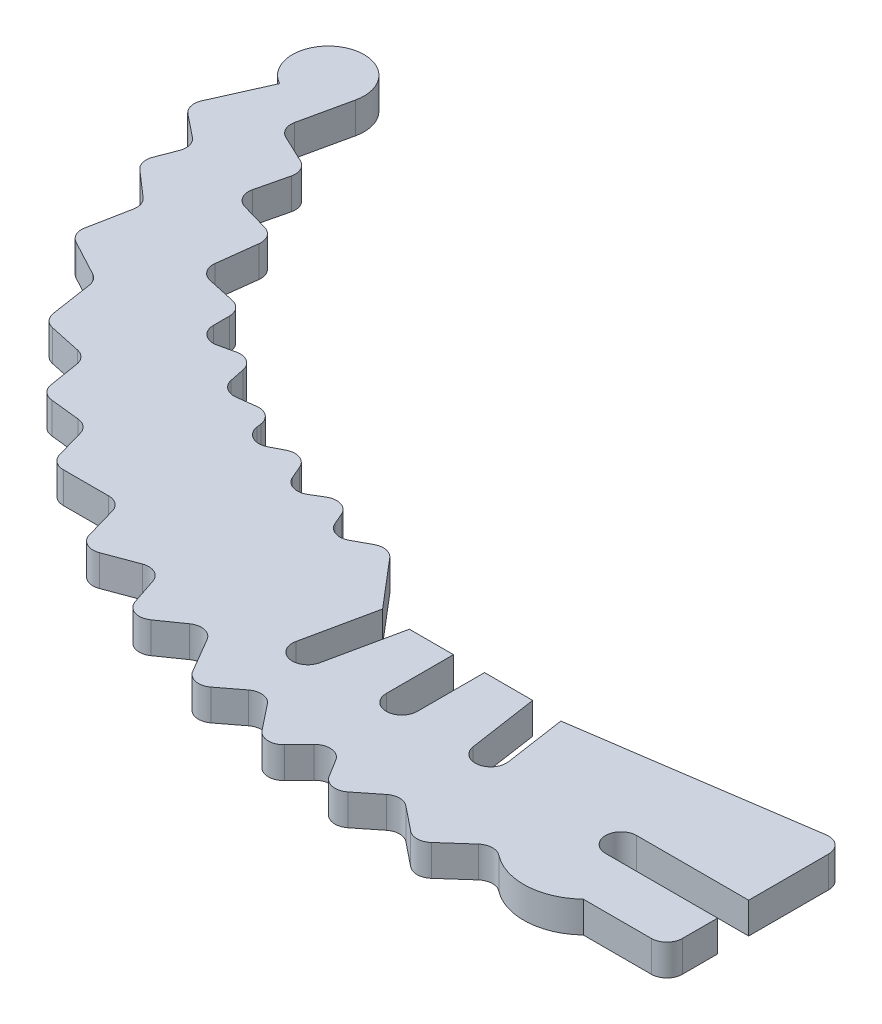
SolidWorks part; units mm, degrees
ref_plane "Front Plane" through (0, 0, 0) normal (0, 0, 1) x (1, 0, 0)
ref_plane "Top Plane" through (0, 0, 0) normal (0, 1, 0) x (1, 0, 0)
ref_plane "Right Plane" through (0, 0, 0) normal (1, 0, 0) x (0, 0, -1)
sketch "Sketch1" plane through (0, 0, 0) normal (0, 1, 0) x (1, 0, 0)
  line L0 (0, 0) -> (0, -4.9)
  line L1 (0, -4.9) -> (-8.07, -4.9)
  line L2 (0, 0) -> (-10.82, 0)
  line L3 (-10.82, 3) -> (0, 3)
  line L4 (0, 3) -> (0, 12.46)
  line L5 (0, 12.46) -> (-24.05, 8.91)
  line L6 (-24.05, 8.91) -> (-23.1736, 2.973)
  line L7 (-26.1415, 2.5349) -> (-27.1371, 9.28)
  line L8 (-27.1371, 9.28) -> (-31.7871, 9.28)
  line L9 (-31.7871, 9.28) -> (-31.7871, 2.79)
  line L10 (-34.7871, 2.79) -> (-34.7871, 9.28)
  line L11 (-34.7871, 9.28) -> (-39.0471, 9.28)
  line L12 (-39.0471, 9.28) -> (-40.5627, 2.1456)
  line L13 (-43.4973, 2.769) -> (-42.0291, 9.68)
  line L14 (-25.391, -4.9) -> (-29.72, -8.34)
  line L15 (-25.391, -4.9) -> (-21.1, -8.34)
  line L16 (-21.1, -8.34) -> (-16.72, -4.45)
  line L17 (-29.72, -8.34) -> (-32.6781, -3.5649)
  line L18 (-32.6781, -3.5649) -> (-36.6143, -7.6594)
  line L19 (-36.6143, -7.6594) -> (-40.5627, -2.6716)
  line L20 (-40.5627, -2.6716) -> (-45.1253, -6.1674)
  line L21 (-45.1253, -6.1674) -> (-48.7727, 0.0558)
  line L22 (-48.7727, 0.0558) -> (-53.9516, -3.5649)
  line L23 (-53.9516, -3.5649) -> (-55.9384, 2.3778)
  line L24 (-55.9384, 2.3778) -> (-61.9367, 0.1499)
  line L25 (-61.9367, 0.1499) -> (-63.5828, 5.91)
  line L26 (-63.5828, 5.91) -> (-70.22, 5.91)
  line L27 (-70.22, 5.91) -> (-71.6049, 10.7561)
  line L30 (-90.9412, 48.643) -> (-93.7301, 42.391)
  line L31 (-93.7301, 42.391) -> (-89.7941, 39.2536)
  line L32 (-89.7941, 39.2536) -> (-91.2772, 35.3746)
  line L33 (-91.2772, 35.3746) -> (-87.3412, 31.952)
  line L34 (-87.3412, 31.952) -> (-88.4821, 26.0765)
  line L35 (-88.4821, 26.0765) -> (-83.3829, 23.343)
  line L36 (-83.3829, 23.343) -> (-82.4925, 17.4771)
  line L37 (-82.4925, 17.4771) -> (-77.4337, 16.398)
  line L38 (-77.4337, 16.398) -> (-76.6075, 11.2974)
  line L39 (-76.6075, 11.2974) -> (-71.6049, 10.7561)
  line L40 (-42.0291, 9.68) -> (-46.7529, 15.232)
  line L41 (-46.7529, 15.232) -> (-50.8382, 13.0298)
  line L42 (-50.8382, 13.0298) -> (-52.6175, 17.1958)
  line L43 (-52.6175, 17.1958) -> (-56.7126, 14.7643)
  line L44 (-56.7126, 14.7643) -> (-58.5391, 19.0289)
  line L46 (-68.1937, 20.1379) -> (-69.0729, 24.4434)
  line L47 (-69.0729, 24.4434) -> (-73.9183, 23.343)
  line L50 (-73.9183, 23.343) -> (-73.9183, 27.97)
  line L51 (-73.9183, 27.97) -> (-79.1759, 29.1242)
  line L52 (-79.1759, 29.1242) -> (-78.3946, 35.5358)
  line L53 (-78.3946, 35.5358) -> (-83.7091, 37.0712)
  line L54 (-83.7091, 37.0712) -> (-82.3686, 42.6654)
  line L55 (-82.3686, 42.6654) -> (-87.2173, 44.9586)
  line L56 (-87.2173, 44.9586) -> (-85.9035, 50.9432)
  line L57 (-68.1937, 20.1379) -> (-63.5706, 20.7366)
  line L58 (-63.5706, 20.7366) -> (-63.0258, 16.7266)
  line L59 (-63.0258, 16.7266) -> (-58.5391, 19.0289)
  arc A0 (-10.82, 0) -> (-10.82, 3) centre (-10.82, 1.5) cw
  arc A1 (-23.1736, 2.973) -> (-26.1415, 2.5349) centre (-24.6576, 2.7539) cw
  arc A2 (-31.7871, 2.79) -> (-34.7871, 2.79) centre (-33.2871, 2.79) cw
  arc A3 (-40.5627, 2.1456) -> (-43.4973, 2.769) centre (-42.03, 2.4573) cw
  arc A4 (-8.07, -4.9) -> (-16.72, -4.45) centre (-12.1828, -0.5957) cw
  arc A5 (-91.5, 54.35) -> (-12.32, 1.5) centre (-27.0029, 65.2409) ccw construction
  arc A6 (-85.9035, 50.9432) -> (-90.9412, 48.643) centre (-89.2866, 51.6858) ccw
  point P7 (-12.32, 1.5)
  point P14 (-24.4385, 1.27)
  point P25 (-33.2871, 1.29)
  point P27 (-21.1, -8.34)
  point P28 (-42.3417, 0.99)
  point P29 (-29.72, -8.34)
  point P30 (-91.5, 54.35)
  point P38 (-70.22, 5.91)
  dimension "D4" = 1.5
  dimension "D14" = 42.03
  dimension "D26" = 5.9533
  dimension "D28" = 65.4101
  dimension "D29" = 3.4636
  dimension "D1" = 4.9
  dimension "D2" = 9.46
  dimension "D3" = 12.32
  dimension "D5" = 5.91
  dimension "D6" = 24.05
  dimension "D7" = 8.07
  dimension "D8" = 7.64
  dimension "D9" = 6.28
  dimension "D10" = 4.65
  dimension "D11" = 4.26
  dimension "D12" = 7.99
  dimension "D13" = 8.29
  dimension "D15" = 0.4
  dimension "D16" = 91.5
  dimension "D17" = 51.35
  dimension "D18" = 8.34
  dimension "D19" = 21.1
  dimension "D20" = 29.72
  dimension "D21" = 16.72
  dimension "D22" = 4.45
  dimension "D23" = 70.22
  dimension "D24" = 2.91
  dimension "D25" = 15.31
  dimension "D27" = 6.26
  dimension "D30" = 25.391
  dimension "D31" = 32.6781
  dimension "D32" = 36.6143
  dimension "D33" = 45.1253
  dimension "D34" = 46.7529
  dimension "D35" = 48.7727
  dimension "D36" = 50.8382
  dimension "D37" = 52.6175
  dimension "D38" = 53.9516
  dimension "D39" = 55.9384
  dimension "D40" = 56.7126
  dimension "D41" = 58.5391
  dimension "D42" = 61.9367
  dimension "D43" = 63.0258
  dimension "D44" = 63.5706
  dimension "D45" = 63.5828
  dimension "D46" = 68.1937
  dimension "D47" = 69.0729
  dimension "D48" = 71.6049
  dimension "D49" = 73.9183
  dimension "D50" = 76.6075
  dimension "D51" = 77.4337
  dimension "D52" = 78.3946
  dimension "D53" = 79.1759
  dimension "D54" = 82.3686
  dimension "D55" = 82.4925
  dimension "D56" = 83.3829
  dimension "D57" = 83.7091
  dimension "D58" = 85.9035
  dimension "D59" = 87.2173
  dimension "D60" = 87.3412
  dimension "D61" = 88.4821
  dimension "D62" = 89.2866
  dimension "D63" = 89.7941
  dimension "D64" = 90.9412
  dimension "D65" = 91.2772
  dimension "D66" = 93.7301
  dimension "D67" = 0.0558
  dimension "D68" = 0.1499
  dimension "D69" = 2.3778
  dimension "D70" = 27.97
  dimension "D71" = 11.2974
  dimension "D72" = 13.0298
  dimension "D73" = 14.7643
  dimension "D74" = 16.398
  dimension "D75" = 16.7266
  dimension "D76" = 17.1958
  dimension "D77" = 17.4771
  dimension "D78" = 19.0289
  dimension "D79" = 20.1379
  dimension "D80" = 20.7366
  dimension "D81" = 23.343
  dimension "D82" = 24.4434
  dimension "D83" = 26.0765
  dimension "D86" = 31.952
  dimension "D87" = 35.3746
  dimension "D88" = 35.5358
  dimension "D89" = 37.0712
  dimension "D90" = 42.391
  dimension "D91" = 42.6654
  dimension "D92" = 2.6716
  dimension "D93" = 3.5649
  dimension "D94" = 6.1674
  dimension "D95" = 7.6594
extrude "Boss-Extrude1" add sketch "Sketch1" along normal blind 3
fillet "Fillet1" radius 1.5 42 edges at (-69.0729, 1.5, -24.4434) (-73.9183, 1.5, -23.343) (-73.9183, 1.5, -27.97) (-79.1759, 1.5, -29.1242) (-78.3946, 1.5, -35.5358) (-83.7091, 1.5, -37.0712) (-82.3686, 1.5, -42.6654) (-87.2173, 1.5, -44.9586) (-93.7301, 1.5, -42.391) (-89.7941, 1.5, -39.2536) (-91.2772, 1.5, -35.3746) (-87.3412, 1.5, -31.952) (-88.4821, 1.5, -26.0765) (-83.3829, 1.5, -23.343) (-82.4925, 1.5, -17.4771) (-77.4337, 1.5, -16.398) (-76.6075, 1.5, -11.2974) (-71.6049, 1.5, -10.7561) (-70.22, 1.5, -5.91) (-63.5828, 1.5, -5.91) (-61.9367, 1.5, -0.1499) (-55.9384, 1.5, -2.3778) (-53.9516, 1.5, 3.5649) (-48.7727, 1.5, -0.0558) (-45.1253, 1.5, 6.1674) (-40.5627, 1.5, 2.6716) (-36.6143, 1.5, 7.6594) (-32.6781, 1.5, 3.5649) (-29.72, 1.5, 8.34) (-25.391, 1.5, 4.9) (-16.72, 1.5, 4.45) (-21.1, 1.5, 8.34) (0, 1.5, 4.9) (0, 1.5, -12.46) (-46.7529, 1.5, -15.232) (-50.8382, 1.5, -13.0298) (-52.6175, 1.5, -17.1958) (-56.7126, 1.5, -14.7643) (-58.5391, 1.5, -19.0289) (-63.0258, 1.5, -16.7266) (-63.5706, 1.5, -20.7366) (-68.1937, 1.5, -20.1379)
